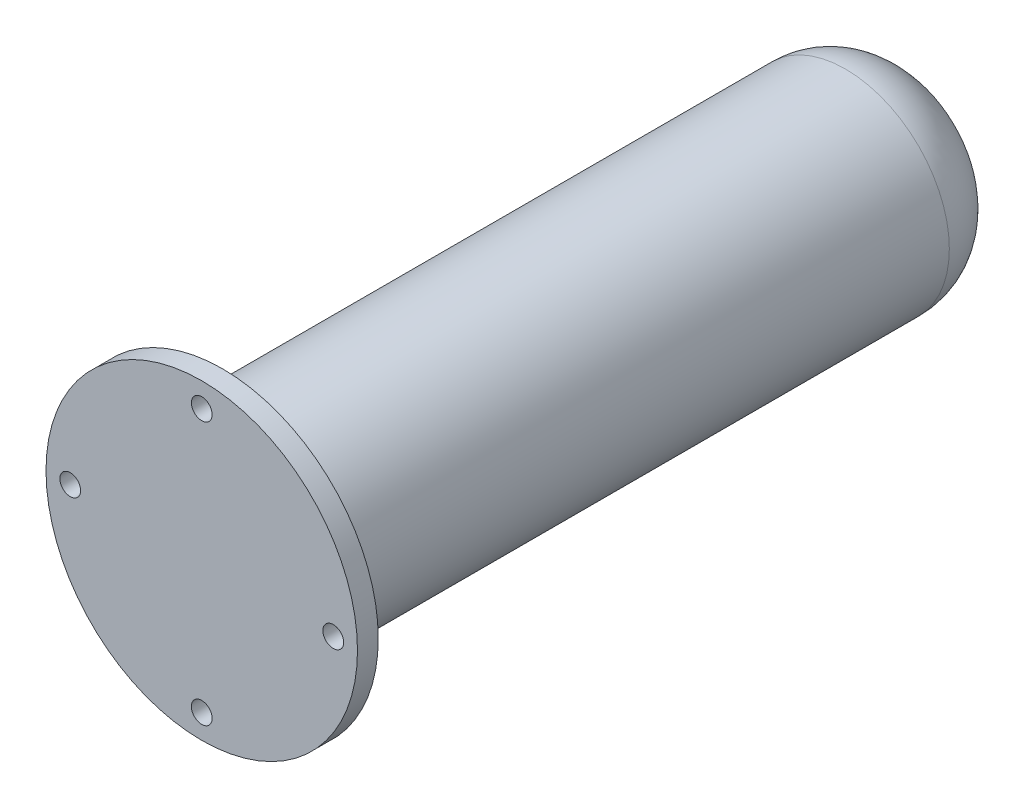
SolidWorks part; units mm, degrees
ref_plane "Plan de face" through (0, 0, 0) normal (0, 0, 1) x (1, 0, 0)
ref_plane "Plan de dessus" through (0, 0, 0) normal (0, 1, 0) x (1, 0, 0)
ref_plane "Plan de droite" through (0, 0, 0) normal (1, 0, 0) x (0, 0, -1)
sketch "Esquisse1" plane through (0, 0, 0) normal (0, 0, 1) x (1, 0, 0)
  circle A0 centre (0, 0) radius 22.5
  circle A1 centre (0, 0) radius 19 construction
  circle A2 centre (0, 19) radius 1.5
  circle A3 centre (19, 0) radius 1.5
  circle A4 centre (0, -19) radius 1.5
  circle A5 centre (-19, 0) radius 1.5
  point P15 (0, 0)
  dimension "D1" = 38
  dimension "D2" = 45
  dimension "D4" = 3
  dimension "D3" = 4
extrude "Boss.-Extru.1" add sketch "Esquisse1" along normal blind 3
sketch "Esquisse2" plane through (0, 0, 0) normal (0, 0, -1) x (-1, 0, 0)
  circle A0 centre (0, 0) radius 15
  dimension "D1" = 30
extrude "Boss.-Extru.2" add sketch "Esquisse2" along normal blind 100
fillet "Congé1" radius 10 1 edges at (-15, 0, -100)
